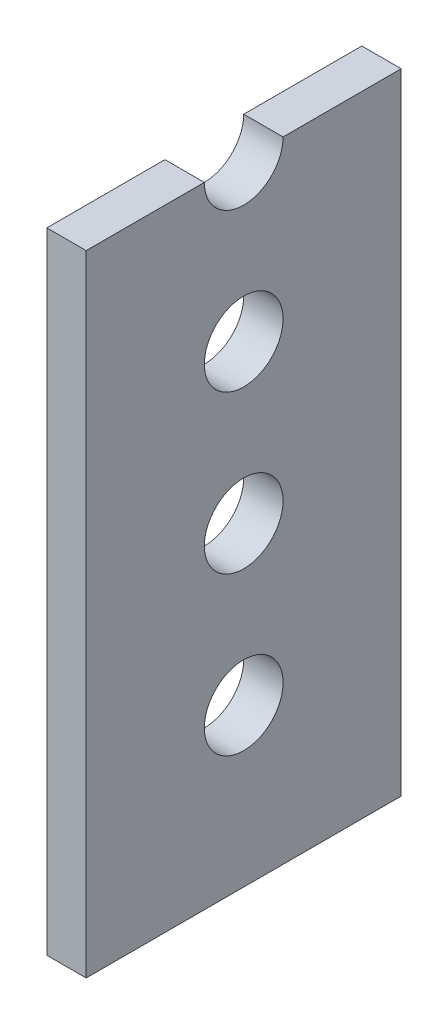
SolidWorks part; units mm, degrees
ref_plane "Front Plane" through (0, 0, 0) normal (0, 0, 1) x (1, 0, 0)
ref_plane "Top Plane" through (0, 0, 0) normal (0, 1, 0) x (1, 0, 0)
ref_plane "Right Plane" through (0, 0, 0) normal (1, 0, 0) x (0, 0, -1)
sketch "Sketch1" plane through (0, 0, 0) normal (1, 0, 0) x (0, 0, -1)
  line L1 (-12.7, -698.5) -> (12.7, -698.5)
  line L2 (-12.7, -698.5) -> (-12.7, 698.5)
  line L3 (-12.7, 698.5) -> (12.7, 698.5)
  line L4 (12.7, -698.5) -> (12.7, 698.5)
  line L5 (-12.7, -698.5) -> (12.7, 698.5) construction
  line L6 (-12.7, 698.5) -> (12.7, -698.5) construction
  circle A0 centre (0, -685.8) radius 3.175
  circle A1 centre (0, -673.1) radius 3.175
  circle A2 centre (0, -660.4) radius 3.175
  circle A3 centre (0, -647.7) radius 3.175
  circle A4 centre (0, -635) radius 3.175
  circle A5 centre (0, -622.3) radius 3.175
  circle A6 centre (0, -609.6) radius 3.175
  circle A7 centre (0, -596.9) radius 3.175
  circle A8 centre (0, -584.2) radius 3.175
  circle A9 centre (0, -571.5) radius 3.175
  circle A10 centre (0, -558.8) radius 3.175
  circle A11 centre (0, -546.1) radius 3.175
  circle A12 centre (0, -533.4) radius 3.175
  circle A13 centre (0, -520.7) radius 3.175
  circle A14 centre (0, -508) radius 3.175
  circle A15 centre (0, -495.3) radius 3.175
  circle A16 centre (0, -482.6) radius 3.175
  circle A17 centre (0, -469.9) radius 3.175
  circle A18 centre (0, -457.2) radius 3.175
  circle A19 centre (0, -444.5) radius 3.175
  circle A20 centre (0, -431.8) radius 3.175
  circle A21 centre (0, -419.1) radius 3.175
  circle A22 centre (0, -406.4) radius 3.175
  circle A23 centre (0, -393.7) radius 3.175
  circle A24 centre (0, -381) radius 3.175
  circle A25 centre (0, -368.3) radius 3.175
  circle A26 centre (0, -355.6) radius 3.175
  circle A27 centre (0, -342.9) radius 3.175
  circle A28 centre (0, -330.2) radius 3.175
  circle A29 centre (0, -317.5) radius 3.175
  circle A30 centre (0, -304.8) radius 3.175
  circle A31 centre (0, -292.1) radius 3.175
  circle A32 centre (0, -279.4) radius 3.175
  circle A33 centre (0, -266.7) radius 3.175
  circle A34 centre (0, -254) radius 3.175
  circle A35 centre (0, -241.3) radius 3.175
  circle A36 centre (0, -228.6) radius 3.175
  circle A37 centre (0, -215.9) radius 3.175
  circle A38 centre (0, -203.2) radius 3.175
  circle A39 centre (0, -190.5) radius 3.175
  circle A40 centre (0, -177.8) radius 3.175
  circle A41 centre (0, -165.1) radius 3.175
  circle A42 centre (0, -152.4) radius 3.175
  circle A43 centre (0, -139.7) radius 3.175
  circle A44 centre (0, -127) radius 3.175
  circle A45 centre (0, -114.3) radius 3.175
  circle A46 centre (0, -101.6) radius 3.175
  circle A47 centre (0, -88.9) radius 3.175
  circle A48 centre (0, -76.2) radius 3.175
  circle A49 centre (0, -63.5) radius 3.175
  circle A50 centre (0, -50.8) radius 3.175
  circle A51 centre (0, -38.1) radius 3.175
  circle A52 centre (0, -25.4) radius 3.175
  circle A53 centre (0, -12.7) radius 3.175
  circle A54 centre (0, 0) radius 3.175
  circle A55 centre (0, 12.7) radius 3.175
  circle A56 centre (0, 25.4) radius 3.175
  circle A57 centre (0, 38.1) radius 3.175
  circle A58 centre (0, 50.8) radius 3.175
  circle A59 centre (0, 63.5) radius 3.175
  circle A60 centre (0, 76.2) radius 3.175
  circle A61 centre (0, 88.9) radius 3.175
  circle A62 centre (0, 101.6) radius 3.175
  circle A63 centre (0, 114.3) radius 3.175
  circle A64 centre (0, 127) radius 3.175
  circle A65 centre (0, 139.7) radius 3.175
  circle A66 centre (0, 152.4) radius 3.175
  circle A67 centre (0, 165.1) radius 3.175
  circle A68 centre (0, 177.8) radius 3.175
  circle A69 centre (0, 190.5) radius 3.175
  circle A70 centre (0, 203.2) radius 3.175
  circle A71 centre (0, 215.9) radius 3.175
  circle A72 centre (0, 228.6) radius 3.175
  circle A73 centre (0, 241.3) radius 3.175
  circle A74 centre (0, 254) radius 3.175
  circle A75 centre (0, 266.7) radius 3.175
  circle A76 centre (0, 279.4) radius 3.175
  circle A77 centre (0, 292.1) radius 3.175
  circle A78 centre (0, 304.8) radius 3.175
  circle A79 centre (0, 317.5) radius 3.175
  circle A80 centre (0, 330.2) radius 3.175
  circle A81 centre (0, 342.9) radius 3.175
  circle A82 centre (0, 355.6) radius 3.175
  circle A83 centre (0, 368.3) radius 3.175
  circle A84 centre (0, 381) radius 3.175
  circle A85 centre (0, 393.7) radius 3.175
  circle A86 centre (0, 406.4) radius 3.175
  circle A87 centre (0, 419.1) radius 3.175
  circle A88 centre (0, 431.8) radius 3.175
  circle A89 centre (0, 444.5) radius 3.175
  circle A90 centre (0, 457.2) radius 3.175
  circle A91 centre (0, 469.9) radius 3.175
  circle A92 centre (0, 482.6) radius 3.175
  circle A93 centre (0, 495.3) radius 3.175
  circle A94 centre (0, 508) radius 3.175
  circle A95 centre (0, 520.7) radius 3.175
  circle A96 centre (0, 533.4) radius 3.175
  circle A97 centre (0, 546.1) radius 3.175
  circle A98 centre (0, 558.8) radius 3.175
  circle A99 centre (0, 571.5) radius 3.175
  circle A100 centre (0, 584.2) radius 3.175
  circle A101 centre (0, 596.9) radius 3.175
  circle A102 centre (0, 609.6) radius 3.175
  circle A103 centre (0, 622.3) radius 3.175
  circle A104 centre (0, 635) radius 3.175
  circle A105 centre (0, 647.7) radius 3.175
  circle A106 centre (0, 660.4) radius 3.175
  circle A107 centre (0, 673.1) radius 3.175
  circle A108 centre (0, 685.8) radius 3.175
  point P0 (0, 0)
  dimension "D1" = 109
extrude "Boss-Extrude1" add sketch "Sketch1" along normal blind 3.175
sketch "Sketch2" plane through (3.175, 0, 0) normal (1, 0, 0) x (0, 0, -1)
  line L0 (12.7, -698.5) -> (12.7, 698.5) construction
  line L1 (-12.7, 698.5) -> (12.7, 698.5)
  line L2 (-12.7, 698.5) -> (-12.7, -647.7)
  line L3 (-12.7, -647.7) -> (12.7, -647.7)
  line L4 (12.7, 698.5) -> (12.7, -647.7)
extrude "Cut-Extrude1" cut sketch "Sketch2" against normal through all both and the other way through all
